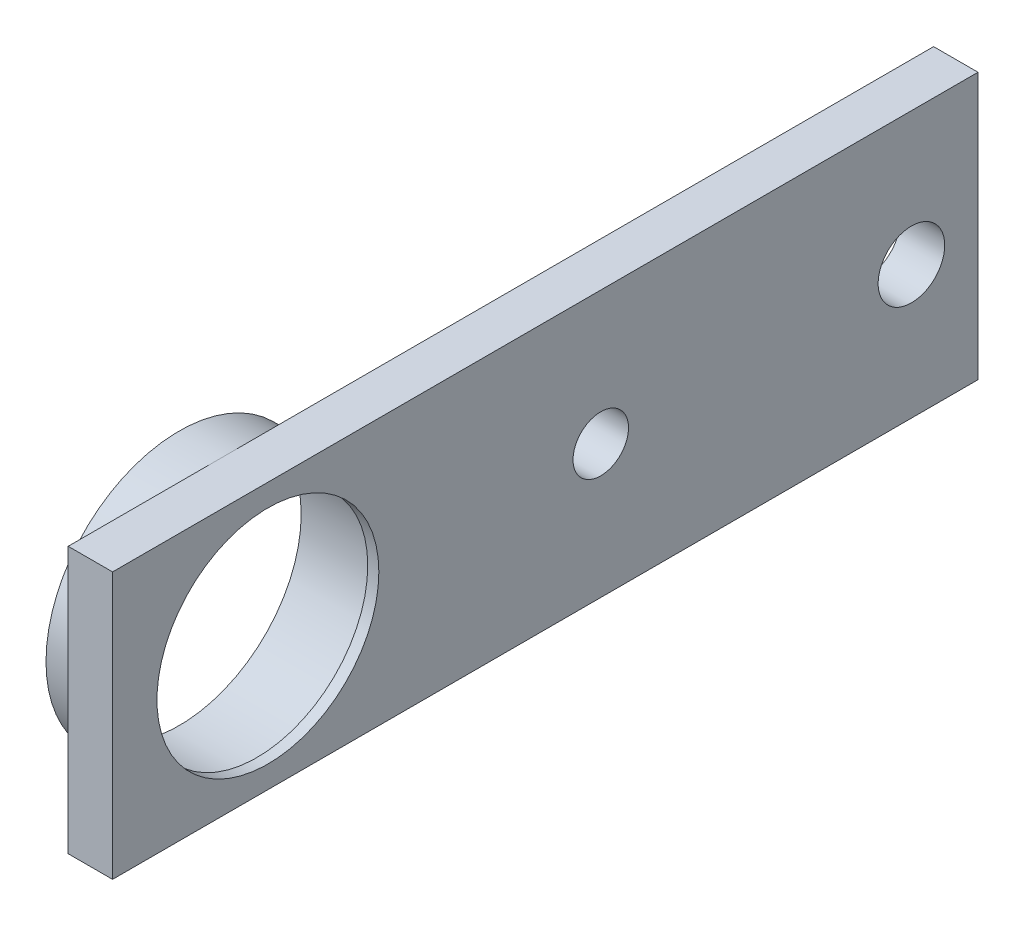
SolidWorks part; units mm, degrees
ref_plane "Front Plane" through (0, 0, 0) normal (0, 0, 1) x (1, 0, 0)
ref_plane "Top Plane" through (0, 0, 0) normal (0, 1, 0) x (1, 0, 0)
ref_plane "Right Plane" through (0, 0, 0) normal (1, 0, 0) x (0, 0, -1)
sketch "Sketch1" plane through (0, 0, 0) normal (1, 0, 0) x (0, 0, -1)
  line L0 (0, 19.05) -> (123.825, 19.05) construction
  line L1 (0, 0) -> (123.825, 0)
  line L2 (0, 0) -> (0, 38.1)
  line L3 (0, 38.1) -> (123.825, 38.1)
  line L4 (123.825, 0) -> (123.825, 38.1)
  circle A0 centre (22.225, 19.05) radius 17.4625
  circle A1 centre (69.85, 19.05) radius 3.9687
  circle A2 centre (114.3, 19.05) radius 4.7625
  dimension "D3" = 34.925
  dimension "D6" = 7.9375
  dimension "D8" = 9.525
  dimension "D1" = 38.1
  dimension "D2" = 9.525
  dimension "D4" = 22.225
  dimension "D5" = 47.625
  dimension "D7" = 44.45
extrude "Boss-Extrude1" add sketch "Sketch1" along normal blind 6.35
sketch "Sketch2" [suppressed] plane through (0, 0, 0) normal (-1, 0, 0) x (0, 0, 1)
  circle A0 centre (-22.225, 19.05) radius 17.4625 construction
  circle A1 centre (-22.225, 19.05) radius 17.4625
  circle A2 centre (-22.225, 19.05) radius 15.875
  dimension "D1" = 1.5875
extrude "Boss-Extrude2" [suppressed] add sketch "Sketch2" against normal blind 1.5875
sketch "Sketch3" plane through (6.35, 0, 0) normal (1, 0, 0) x (0, 0, -1)
  circle A0 centre (22.225, 19.05) radius 17.4625 construction
  circle A1 centre (22.225, 19.05) radius 17.4625
  circle A2 centre (22.225, 19.05) radius 15.875
  dimension "D1" = 1.5875
extrude "Boss-Extrude3" add sketch "Sketch3" against normal blind 1.5875
sketch "Sketch4" [suppressed] plane through (6.35, 0, 0) normal (1, 0, 0) x (0, 0, -1)
  line L0 (123.825, 38.1) -> (0, 38.1) construction
  circle A0 centre (22.225, 19.05) radius 17.4625 construction
  circle A1 centre (22.225, 19.05) radius 17.4625
  circle A2 centre (22.225, 19.05) radius 19.05
extrude "Boss-Extrude4" [suppressed] add sketch "Sketch4" along normal blind 6.35
sketch "Sketch5" plane through (0, 0, 0) normal (-1, 0, 0) x (0, 0, 1)
  line L0 (-123.825, 38.1) -> (0, 38.1) construction
  circle A0 centre (-22.225, 19.05) radius 17.4625 construction
  circle A1 centre (-22.225, 19.05) radius 17.4625
  circle A2 centre (-22.225, 19.05) radius 19.05
extrude "Boss-Extrude5" add sketch "Sketch5" along normal blind 6.35
